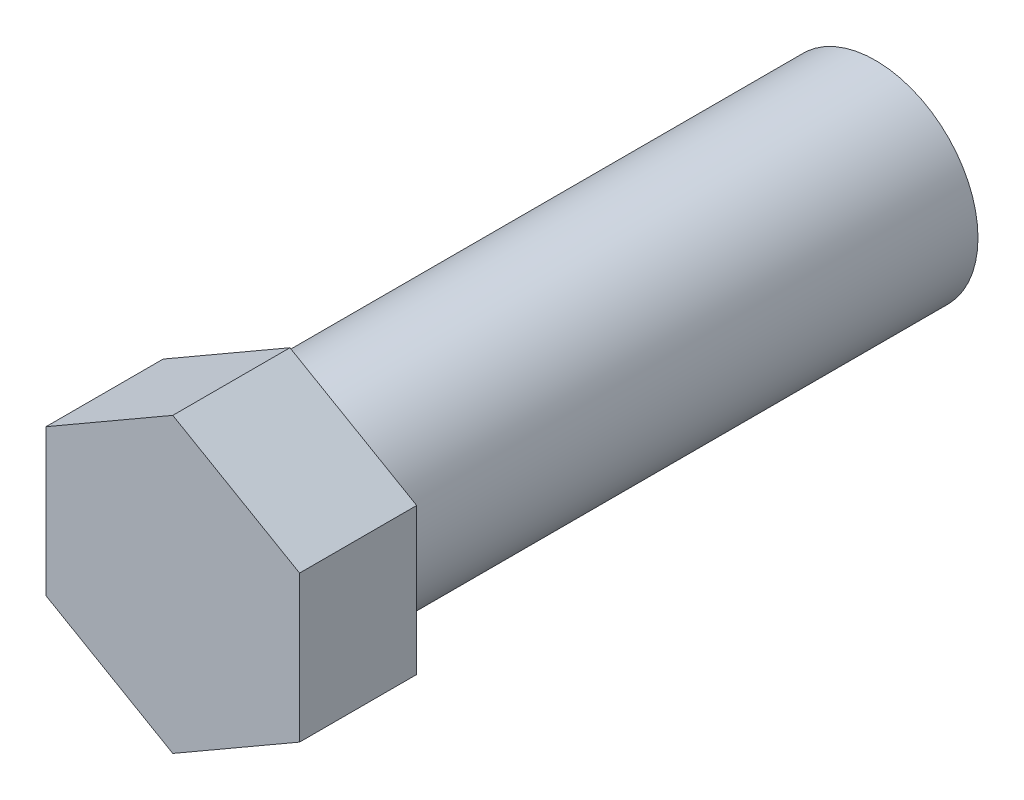
SolidWorks part; units mm, degrees
ref_plane "Plan de face" through (0, 0, 0) normal (0, 0, 1) x (1, 0, 0)
ref_plane "Plan de dessus" through (0, 0, 0) normal (0, 1, 0) x (1, 0, 0)
ref_plane "Plan de droite" through (0, 0, 0) normal (1, 0, 0) x (0, 0, -1)
sketch "Esquisse1" plane through (0, 0, 0) normal (0, 0, 1) x (1, 0, 0)
  line L0 (0, 0) -> (0, 1.75)
  circle A0 centre (0, 0) radius 1.75
  dimension "D1" = 1.75
extrude "Boss.-Extru.1" add sketch "Esquisse1" along normal blind 10
sketch "Esquisse2" plane through (0, 0, 10) normal (0, 0, 1) x (1, 0, 0)
  line L0 (0, 0) -> (0, 2.5)
  line L2 (0, 2.5) -> (-2.1651, 1.25)
  line L3 (-2.1651, 1.25) -> (-2.1651, -1.25)
  line L4 (-2.1651, -1.25) -> (0, -2.5)
  line L5 (0, -2.5) -> (2.1651, -1.25)
  line L6 (2.1651, -1.25) -> (2.1651, 1.25)
  line L7 (2.1651, 1.25) -> (0, 2.5)
  circle A0 centre (0, 0) radius 2.1651 construction
  dimension "D1" = 2.5
extrude "Boss.-Extru.2" add sketch "Esquisse2" along normal blind 2
